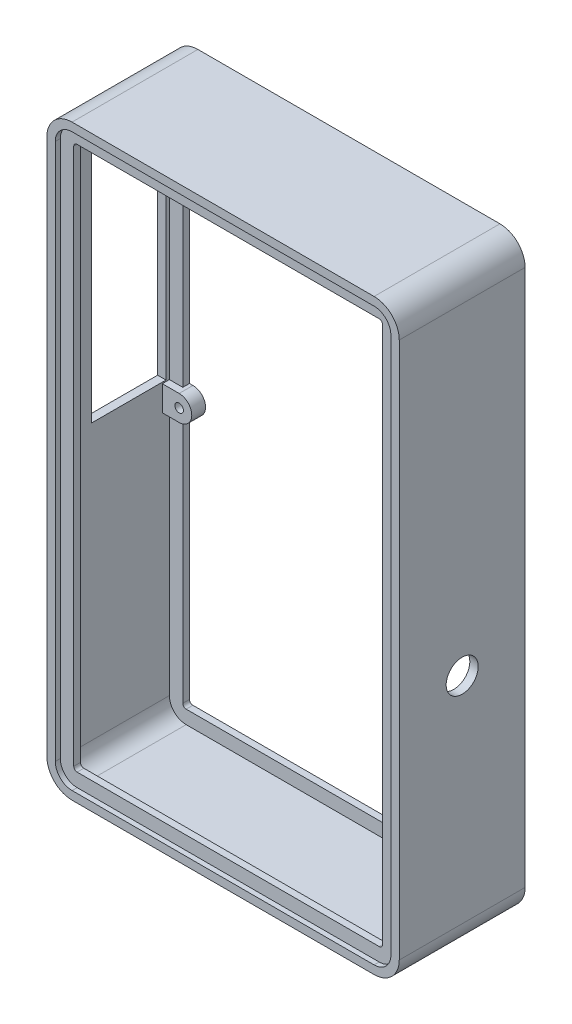
SolidWorks part; units mm, degrees
ref_plane "Front Plane" through (0, 0, 0) normal (0, 0, 1) x (1, 0, 0)
ref_plane "Top Plane" through (0, 0, 0) normal (0, 1, 0) x (1, 0, 0)
ref_plane "Right Plane" through (0, 0, 0) normal (1, 0, 0) x (0, 0, -1)
sketch "Sketch1" plane through (0, 0, 0) normal (0, 0, 1) x (1, 0, 0)
  line L0 (5, 5) -> (5, 345)
  line L1 (0, 0) -> (210, 0)
  line L2 (0, 0) -> (0, 350)
  line L3 (0, 350) -> (210, 350)
  line L4 (210, 0) -> (210, 350)
  line L5 (5, 345) -> (205, 345)
  line L6 (205, 5) -> (205, 345)
  line L7 (5, 5) -> (205, 5)
  dimension "D1" = 5
extrude "Boss-Extrude1" add sketch "Sketch1" along normal blind 75
fillet "Fillet1" radius 15 4 edges at (210, 350, 37.5) (210, 0, 37.5) (0, 0, 37.5) (0, 350, 37.5)
fillet "Fillet2" radius 10 4 edges at (205, 5, 37.5) (5, 5, 37.5) (5, 345, 37.5) (205, 345, 37.5)
ref_plane "Plane1" through (0, 0, 37.5) normal (0, 0, -1) x (-1, 0, 0)
ref_plane "Plane2" through (0, 0, 3) normal (0, 0, -1) x (-1, 0, 0)
sketch "Sketch2" plane through (0, 0, 3) normal (0, 0, -1) x (-1, 0, 0)
  line L0 (-15, 5) -> (-195, 5) construction
  line L1 (-5, 335) -> (-5, 15) construction
  line L2 (-205, 15) -> (-205, 335) construction
  line L3 (-195, 345) -> (-15, 345) construction
  line L4 (-15, 5) -> (-195, 5)
  line L5 (-5, 335) -> (-5, 15)
  line L6 (-205, 15) -> (-205, 335)
  line L7 (-195, 345) -> (-15, 345)
  line L8 (-13, 335) -> (-13, 15)
  line L9 (-195, 337) -> (-15, 337)
  line L10 (-197, 15) -> (-197, 335)
  line L11 (-15, 13) -> (-195, 13)
  arc A0 (-15, 5) -> (-5, 15) centre (-15, 15) ccw construction
  arc A1 (-205, 15) -> (-195, 5) centre (-195, 15) ccw construction
  arc A2 (-5, 335) -> (-15, 345) centre (-15, 335) ccw construction
  arc A3 (-195, 345) -> (-205, 335) centre (-195, 335) ccw construction
  arc A4 (-15, 5) -> (-5, 15) centre (-15, 15) ccw
  arc A5 (-205, 15) -> (-195, 5) centre (-195, 15) ccw
  arc A6 (-5, 335) -> (-15, 345) centre (-15, 335) ccw
  arc A7 (-195, 345) -> (-205, 335) centre (-195, 335) ccw
  arc A8 (-15, 13) -> (-13, 15) centre (-15, 15) ccw
  arc A9 (-13, 335) -> (-15, 337) centre (-15, 335) ccw
  arc A10 (-195, 337) -> (-197, 335) centre (-195, 335) ccw
  arc A11 (-197, 15) -> (-195, 13) centre (-195, 15) ccw
  dimension "D1" = 8
extrude "Boss-Extrude2" add sketch "Sketch2" against normal blind 4
mirror "Mirror1" about plane through (0, 0, 37.5) normal (0, 0, -1) of "Boss-Extrude2"
sketch "Sketch3" plane through (5, 0, 0) normal (1, 0, 0) x (0, 0, -1)
  line L0 (-68, 345) -> (-7, 345) construction
  line L1 (-68, 345) -> (-7, 345)
  line L2 (-7, 345) -> (-7, 337.62)
  line L3 (-7, 337.62) -> (-9, 337.62)
  line L4 (-9, 337.62) -> (-53.5, 337.62)
  line L5 (-53.5, 337.62) -> (-53.5, 178.87)
  line L7 (-53.5, 178.87) -> (-9, 178.87)
  line L8 (-53.5, 178.87) -> (-53.5, 337.62)
  line L9 (-53.5, 337.62) -> (-9, 337.62)
  line L10 (-9, 178.87) -> (-9, 337.62)
  line M1 (-7, 335) -> (-68, 335)
extrude "Cut-Extrude1" cut sketch "Sketch3" against normal blind 25 and the other way blind 4 contours L7 L10 L5 M1 | L10 L4 L5 M1
sketch "Sketch4" plane through (5, 0, 0) normal (1, 0, 0) x (0, 0, -1)
  line L0 (-9, 337.62) -> (-9, 335) construction
  line L1 (-9, 337.62) -> (-9, 335)
  line L2 (-9, 335) -> (-7, 335)
  line L3 (-7, 335) -> (-7, 337.62)
  line L4 (-7, 337.62) -> (-9, 337.62)
  line L5 (-7, 337.62) -> (-7, 339.62)
  line L6 (-53.5, 335) -> (-53.5, 337.62) construction
  line L7 (-53.5, 335) -> (-53.5, 337.62)
  line L8 (-53.5, 335) -> (-55.5, 335)
  line L9 (-53.5, 335) -> (-68, 335) construction
  line L10 (-55.5, 335) -> (-55.5, 337.62)
  line L11 (-55.5, 337.62) -> (-53.5, 337.62)
  line L12 (-55.5, 337.62) -> (-55.5, 339.62)
  line L13 (-55.5, 339.62) -> (-7, 339.62)
  line L14 (-9, 337.62) -> (-53.5, 337.62)
  line M2 (-7, 335) -> (-9, 335)
  line M6 (-53.5, 335) -> (-68, 335)
extrude "Cut-Extrude2" cut sketch "Sketch4" along normal blind 18 contours L11 L10 L7 M6 | L14 L4 L5 L13 L12 L11 | L3 L4 L1 M2
sketch "Sketch5" plane through (0, 0, 7) normal (0, 0, 1) x (1, 0, 0)
  line L0 (30.42, 345) -> (45.42, 345)
  line L1 (5, 15) -> (5, 339.62) construction
  line L2 (170, 170.59) -> (15.06, 170.59)
  line L3 (15, 345) -> (195, 345) construction
  line L4 (205, 335) -> (205, 15) construction
  line L5 (30.42, 328.07) -> (30.42, 345)
  line L6 (30.42, 345) -> (37.92, 345)
  line L7 (45.42, 328.07) -> (45.42, 345)
  line L8 (37.92, 345) -> (45.42, 345)
  line L9 (205, 335) -> (205, 15)
  line L10 (15, 345) -> (195, 345)
  line L11 (162.5, 328.07) -> (162.5, 345)
  line L12 (170, 320.57) -> (205, 320.57)
  line L13 (170, 178.09) -> (205, 178.09)
  line L14 (170, 163.09) -> (205, 163.09)
  line L15 (205, 163.09) -> (205, 178.09)
  line L16 (15.06, 178.09) -> (7.56, 178.09)
  line L17 (7.56, 178.09) -> (7.56, 170.59)
  line L18 (7.56, 170.59) -> (7.56, 163.09)
  line L19 (7.56, 163.09) -> (15.06, 163.09)
  line L20 (7.56, 178.09) -> (5, 178.09)
  line L21 (7.56, 178.09) -> (7.56, 163.09)
  line L22 (7.56, 163.09) -> (5, 163.09)
  line L23 (5, 178.09) -> (5, 163.09)
  circle A0 centre (37.92, 328.07) radius 2.55
  arc A1 (30.42, 328.07) -> (45.42, 328.07) centre (37.92, 328.07) ccw
  circle A2 centre (170, 328.07) radius 2.55
  arc A3 (162.5, 328.07) -> (170, 320.57) centre (170, 328.07) ccw
  arc A4 (205, 335) -> (195, 345) centre (195, 335) ccw construction
  arc A5 (205, 335) -> (195, 345) centre (195, 335) ccw
  circle A6 centre (170, 170.59) radius 2.55
  arc A7 (170, 178.09) -> (170, 163.09) centre (170, 170.59) ccw
  circle A8 centre (15.06, 170.59) radius 2.55
  circle A9 centre (15.06, 170.59) radius 7.5
extrude "Boss-Extrude4" add sketch "Sketch5" along normal blind 4.23 and the other way up to surface
sketch "Sketch6" plane through (210, 0, 0) normal (1, 0, 0) x (0, 0, -1)
  line L0 (-37.5, 0) -> (-37.5, 143)
  line L1 (0, 0) -> (-75, 0) construction
  circle A0 centre (-37.5, 143) radius 9.55
extrude "Cut-Extrude4" cut sketch "Sketch6" against normal blind 22
sketch "Sketch7" plane through (0, 0, 11.23) normal (0, 0, 1) x (1, 0, 0)
  line L1 (13, 169.087) -> (13, 172.093)
  line L2 (13, 169.087) -> (13, 172.093)
  arc A1 (13, 172.093) -> (13, 169.087) centre (15.06, 170.59) ccw
  arc A2 (13, 172.093) -> (13, 169.087) centre (15.06, 170.59) ccw
  dimension "D1" = 0
extrude "Cut-Extrude5" cut sketch "Sketch7" against normal blind 22
